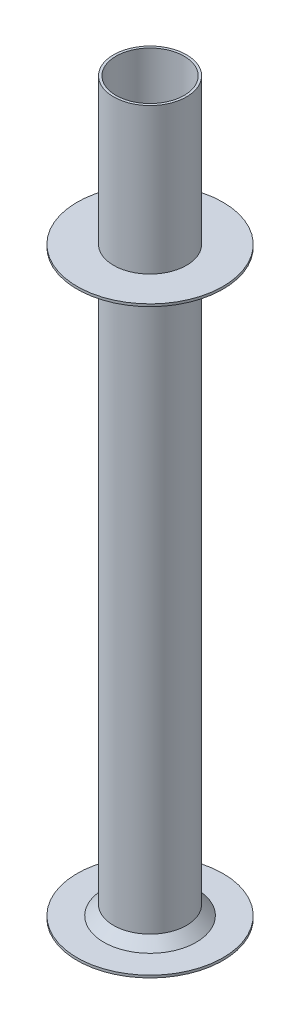
SolidWorks part; units mm, degrees
material "Brass"
ref_plane "前视基准面" through (0, 0, 0) normal (0, 0, 1) x (1, 0, 0)
ref_plane "上视基准面" through (0, 0, 0) normal (0, 1, 0) x (1, 0, 0)
ref_plane "右视基准面" through (0, 0, 0) normal (1, 0, 0) x (0, 0, -1)
sketch "Sketch1" plane through (0, 0, 0) normal (0, 1, 0) x (1, 0, 0)
  circle A0 centre (0, 0) radius 75
  dimension "D1" = 150
extrude "Boss-Extrude1" add sketch "Sketch1" along normal blind 1500
sketch "Sketch2" plane through (0, 0, 0) normal (0, 0, 1) x (1, 0, 0)
  line L0 (-358.4656, 0) -> (313.8264, 0) construction
  line L1 (0, 0) -> (150, 0)
  line L2 (150, 0) -> (150, 5)
  line L3 (150, 5) -> (95, 5)
  line L4 (95, 5) -> (0, 100)
  line L5 (0, 100) -> (0, 0)
  line L6 (-358.4656, 1200) -> (313.8264, 1200) construction
  line L7 (0, -133.2917) -> (0, 1591.0059) construction
  line L8 (0, 1200) -> (150, 1200)
  line L9 (150, 1200) -> (150, 1195)
  line L10 (150, 1195) -> (95, 1195)
  line L11 (95, 1195) -> (0, 1100)
  line L12 (0, 1100) -> (0, 1200)
  dimension "D1" = 150
  dimension "D2" = 5
  dimension "D3" = 55
  dimension "D4" = 45
  dimension "D6" = 150
  dimension "D7" = 5
  dimension "D8" = 55
  dimension "D9" = 45
  dimension "D10" = 90
  dimension "D5" = 1200
revolve "Revolve1" add sketch "Sketch2" angle 360 about L7
sketch "Sketch3" plane through (0, 1500, 0) normal (0, 1, 0) x (1, 0, 0)
  circle A0 centre (0, 0) radius 75 construction
  circle A1 centre (0, 0) radius 70
  dimension "D1" = 150
  dimension "D2" = 5
extrude "Cut-Extrude1" cut sketch "Sketch3" against normal through all
